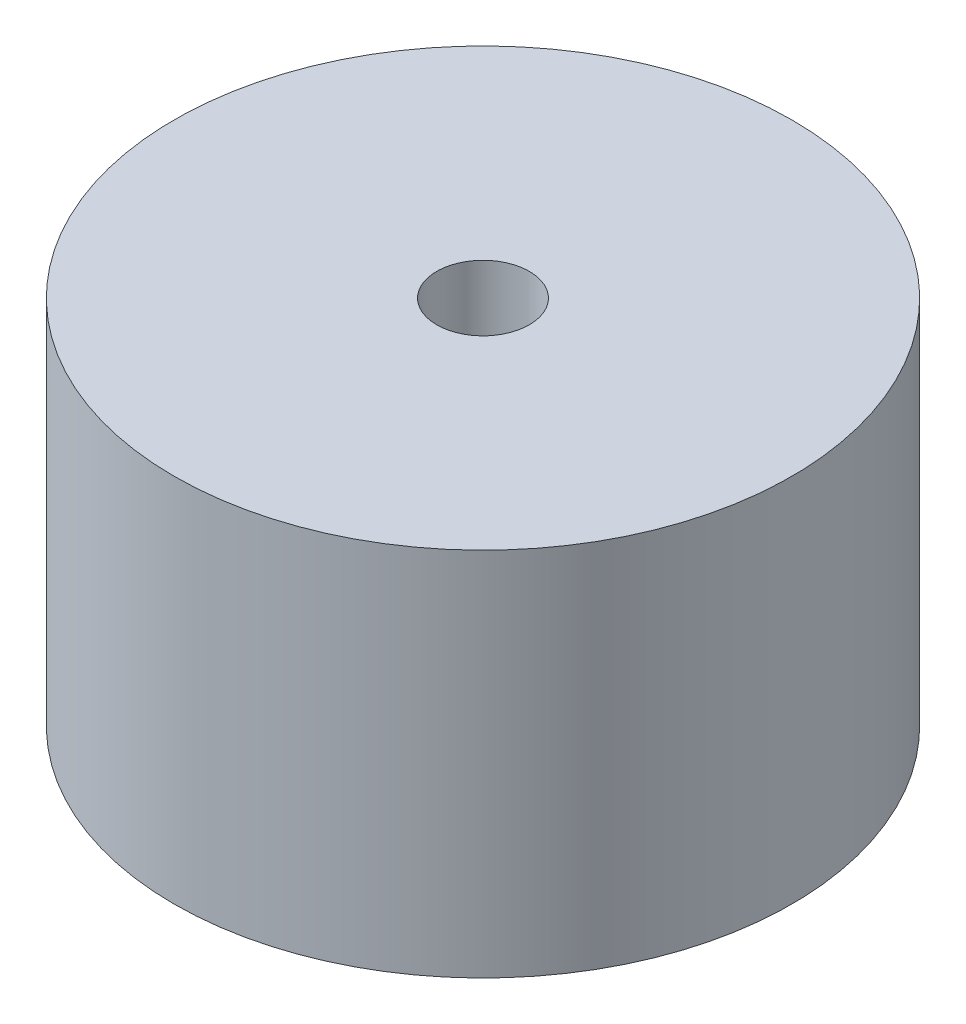
SolidWorks part; units mm, degrees
ref_plane "前视基准面" through (0, 0, 0) normal (0, 0, 1) x (1, 0, 0)
ref_plane "上视基准面" through (0, 0, 0) normal (0, 1, 0) x (1, 0, 0)
ref_plane "右视基准面" through (0, 0, 0) normal (1, 0, 0) x (0, 0, -1)
sketch "Sketch1" plane through (0, 0, 0) normal (0, 1, 0) x (1, 0, 0)
  circle A0 centre (0, 0) radius 10
  circle A1 centre (0, 0) radius 1.5
  dimension "D1" = 20
  dimension "D2" = 3
extrude "Boss-Extrude1" add sketch "Sketch1" along normal blind 12
